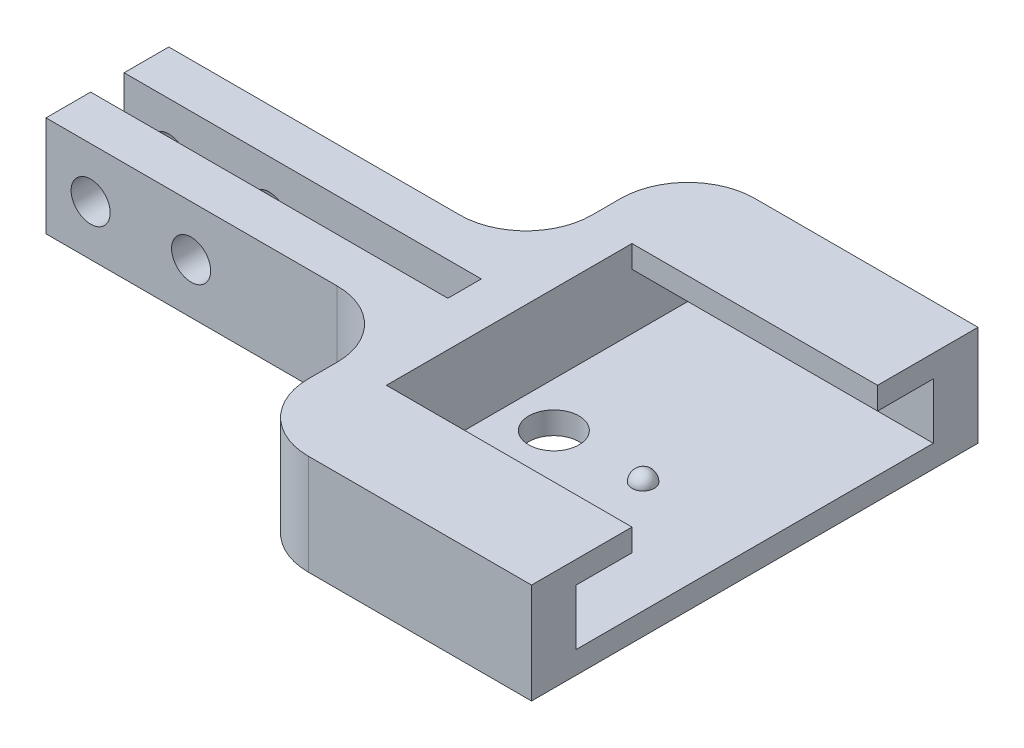
SolidWorks part; units mm, degrees
ref_plane "Front" through (0, 0, 0) normal (0, 0, 1) x (1, 0, 0)
ref_plane "Top" through (0, 0, 0) normal (0, 1, 0) x (1, 0, 0)
ref_plane "Right" through (0, 0, 0) normal (1, 0, 0) x (0, 0, -1)
sketch "Croquis1" plane through (0, 0, 0) normal (0, 1, 0) x (1, 0, 0)
  line L0 (-223.043, 0) -> (10929.1056, 0) construction
  line L1 (0, -223.043) -> (0, 10929.1056) construction
  line L2 (-223.043, -2.5) -> (10929.1056, -2.5) construction
  line L3 (-5, -10) -> (5, -10)
  line L4 (-8, -992.5198) -> (-8, 49007.4802) construction
  line L5 (-5, 10) -> (5, 10)
  line L6 (5, 10) -> (5, -10)
  line L7 (-5, -10) -> (5, 10) construction
  line L8 (-5, 10) -> (5, -10) construction
  line L9 (-223.043, 2.5) -> (10929.1056, 2.5) construction
  line L10 (-24, 0.75) -> (-24, 2.75)
  line L11 (-715.1068, 709.8568) -> (34640.2323, -34645.4823) construction
  line L17 (-24, 2.75) -> (-10.9538, 2.75)
  line L18 (-24, 0.75) -> (-8, 0.75)
  line L19 (-8, 0.75) -> (-8, -0.75)
  line L20 (-8, -0.75) -> (-24, -0.75)
  line L21 (-8, 5.7038) -> (-8, 7)
  line L22 (-8, -5.7038) -> (-8, -7)
  line L23 (-24, -2.75) -> (-10.9538, -2.75)
  line L24 (-24, -0.75) -> (-24, -2.75)
  arc A0 (-8, 7) -> (-5, 10) centre (-5, 7) cw
  arc A1 (-5, -10) -> (-8, -7) centre (-5, -7) cw
  arc A2 (-8, 5.7038) -> (-10.9538, 2.75) centre (-10.9538, 5.7038) cw
  arc A3 (-8, -5.7038) -> (-10.9538, -2.75) centre (-10.9538, -5.7038) ccw
  point P4 (0, 0)
  point P22 (0, 0)
  point P32 (0.6, 0)
  dimension "D3" = 16
  dimension "D4" = 10
  dimension "D1" = 20
  dimension "D2" = 10
  dimension "D12" = 2
  dimension "D13" = 0.75
  dimension "D9" = 2.5
  dimension "D10" = 2.5
extrude "Saliente-Extruir1" add sketch "Croquis1" along normal blind 4.5
ref_plane "Plano1" through (0, 0, 1.375) normal (0, 0, 1) x (1, 0, 0)
sketch "Croquis7" plane through (0, 0, 2.75) normal (0, 0, 1) x (1, 0, 0)
  line L0 (-1000, 0) -> (49000, 0) construction
  line L1 (-1000.1155, 2.25) -> (48999.8845, 2.25) construction
  line L2 (0, -1000) -> (0, 49000) construction
  line L3 (-24, 4.5) -> (-24, 0) construction
  circle A0 centre (-22, 2.25) radius 0.875
  circle A2 centre (-17.5, 2.25) radius 0.875
  dimension "D2" = 2
  dimension "D3" = 1.75
  dimension "D4" = 1.75
  dimension "D5" = 4.5
  dimension "D1" = 2.25
extrude "Cortar-Extruir4" cut sketch "Croquis7" against normal through all and the other way blind 10
sketch "Croquis2" plane through (0, 4.5, 0) normal (0, 1, 0) x (1, 0, 0)
  line L0 (0, -1000) -> (0, 49000) construction
  line L1 (-1000, 0) -> (49000, 0) construction
  line L2 (-1000, -6.5) -> (49000, -6.5) construction
  line L3 (-1000, 6.5) -> (49000, 6.5) construction
  line L4 (5, -1000) -> (5, 49000) construction
  line L5 (-7, -1000) -> (-7, 49000) construction
  line L6 (-5, 6.5) -> (-1.5, 6.5)
  line L7 (-1.5, 6.5) -> (-1.5, 4.5)
  line L8 (-1.5, 4.5) -> (-5, 4.5)
  line L9 (-5, 4.5) -> (-5, 6.5)
  line L10 (-5, -4.5) -> (-5, -6.5)
  line L11 (-1.5, -4.5) -> (-5, -4.5)
  line L12 (-1.5, -6.5) -> (-1.5, -4.5)
  line L13 (-5, -6.5) -> (-1.5, -6.5)
  line L14 (5, -4.5) -> (5, -6.5)
  line L15 (5, -6.5) -> (1.5, -6.5)
  line L16 (1.5, -6.5) -> (1.5, -4.5)
  line L17 (1.5, -4.5) -> (5, -4.5)
  point P16 (-3.25, 6.5)
  dimension "D5" = 3.5
  dimension "D6" = 2
  dimension "D7" = 1.5
  dimension "D1" = 6.5
  dimension "D2" = 6.5
  dimension "D3" = 5
extrude "Saliente-Extruir2" [suppressed] add sketch "Croquis2" along normal blind 9
sketch "Croquis3" [suppressed] plane through (0, 0, 6.5) normal (0, 0, 1) x (1, 0, 0)
  line L2 (0, -1000) -> (0, 49000) construction
  line L3 (1.5, 12) -> (5, 12) construction
  line L5 (1.5, 12) -> (1.5, 3) construction
  circle A1 centre (3.5, 10) radius 1.125
  dimension "D1" = 2
  dimension "D2" = 2
extrude "Cortar-Extruir1" [suppressed] cut sketch "Croquis3" against normal up to surface (13 mm away)
sketch "Croquis4" [suppressed] plane through (0, 0, 6.5) normal (0, 0, 1) x (1, 0, 0)
  line L0 (-3.25, -993) -> (-3.25, 49007) construction
  line L1 (-5, 12) -> (-1.5, 12) construction
  line L2 (-1007.7153, 10.45) -> (48992.2847, 10.45) construction
  line L4 (-1.5, 12) -> (-1.5, 3) construction
  line L5 (-5, 12) -> (-1.5, 12)
  line L6 (-5, 12) -> (-5, 10.45)
  line L7 (-5, 10.45) -> (-1.5, 10.45)
  line L8 (-1.5, 12) -> (-1.5, 10.45)
  point P5 (-3.25, 12)
  dimension "D1" = 1.55
extrude "Cortar-Extruir2" [suppressed] cut sketch "Croquis4" against normal up to surface (13 mm away)
fillet "Redondeo1" [suppressed] radius 2
sketch "Croquis5" [suppressed] plane through (-5, 0, 0) normal (-1, 0, 0) x (0, 0, 1)
  line L0 (6.5, 12) -> (6.5, 3) construction
  line L1 (4.5, 12) -> (6.5, 12)
  line L2 (4.5, 12) -> (4.5, 8)
  line L3 (4.5, 8) -> (6.5, 8)
  line L4 (6.5, 12) -> (6.5, 8)
  line L5 (0, -1000) -> (0, 49000) construction
  line L6 (-7, 0) -> (7, 0) construction
  line L7 (-4.5, 12) -> (-4.5, 8)
  line L8 (-4.5, 8) -> (-6.5, 8)
  line L9 (-6.5, 12) -> (-6.5, 8)
  line L10 (-4.5, 12) -> (-6.5, 12)
  point P12 (0, 0)
  dimension "D1" = 4
extrude "Saliente-Extruir3" [suppressed] add sketch "Croquis5" along normal blind 4
sketch "Croquis6" [suppressed] plane through (0, 0, 6.5) normal (0, 0, 1) x (1, 0, 0)
  line L0 (-5, 8) -> (-9, 12) construction
  line L1 (-9, 8) -> (-5.25, 12) construction
  line L2 (-9, 12) -> (-1.5, 12) construction
  circle A0 centre (-7, 10) radius 1.125
  dimension "D1" = 2.25
extrude "Cortar-Extruir3" [suppressed] cut sketch "Croquis6" against normal through all
fillet "Redondeo2" [suppressed] radius 1
sketch "Croquis8" plane through (5, 0, 0) normal (1, 0, 0) x (0, 0, -1)
  line L0 (-1000, 0) -> (49000, 0) construction
  line L1 (0, -1000) -> (0, 49000) construction
  line L2 (-8, 1) -> (8, 1)
  line L5 (-8, 1) -> (-8, 3.5)
  line L6 (-8, 3.5) -> (-5.5, 3.5)
  line L7 (-5.5, 3.5) -> (-5.5, 4.5)
  line L8 (-10, 4.5) -> (10, 4.5) construction
  line L9 (-5.5, 4.5) -> (5.5, 4.5)
  line L10 (5.5, 3.5) -> (5.5, 4.5)
  line L11 (8, 3.5) -> (5.5, 3.5)
  line L12 (8, 1) -> (8, 3.5)
  point P8 (0, 1)
  point P15 (0, 4.5)
  dimension "D1" = 1
  dimension "D2" = 16
  dimension "D3" = 2.5
  dimension "D4" = 1
extrude "Cortar-Extruir5" cut sketch "Croquis8" against normal blind 11
sketch "Croquis9" plane through (0, 1, 0) normal (0, 1, 0) x (1, 0, 0)
  line L0 (-1000, 0) -> (49000, 0) construction
  line L1 (0, -1000) -> (0, 49000) construction
  circle A0 centre (-4, 0) radius 1.125
  dimension "D1" = 2.25
  dimension "D2" = 4
extrude "Cortar-Extruir6" cut sketch "Croquis9" against normal through all
sketch "Croquis10" plane through (0, 0, 0) normal (1, 0, 0) x (0, 0, -1)
  line L0 (-1000, 1) -> (49000, 1) construction
  line L1 (-8, 1) -> (8, 1) construction
  line L2 (0, -1000) -> (0, 49000) construction
  line L3 (-5, -998.5) -> (-5, 49001.5) construction
  line L4 (-5.5, 1) -> (-4.5, 1)
  line L5 (5.5, 1) -> (4.5, 1)
  arc A0 (-4.5, 1) -> (-5.5, 1) centre (-5, 1) ccw
  arc A1 (4.5, 1) -> (5.5, 1) centre (5, 1) cw
  point P5 (0, 1)
  dimension "D1" = 1
  dimension "D2" = 5
revolve "Revolución1" [suppressed] add sketch "Croquis10" angle 360 about L0
sketch "Croquis11" plane through (0, 0, 0) normal (1, 0, 0) x (0, 0, -1)
  line L0 (-1000, 1) -> (49000, 1) construction
  line L1 (-8, 1) -> (8, 1) construction
  line L2 (0, -1000) -> (0, 49000) construction
  line L3 (-0.5, 1) -> (0.5, 1)
  arc A0 (0.5, 1) -> (-0.5, 1) centre (0, 1) ccw
  point P5 (0, 1)
  dimension "D1" = 1
revolve "Revolución2" add sketch "Croquis11" angle 360 about L3
